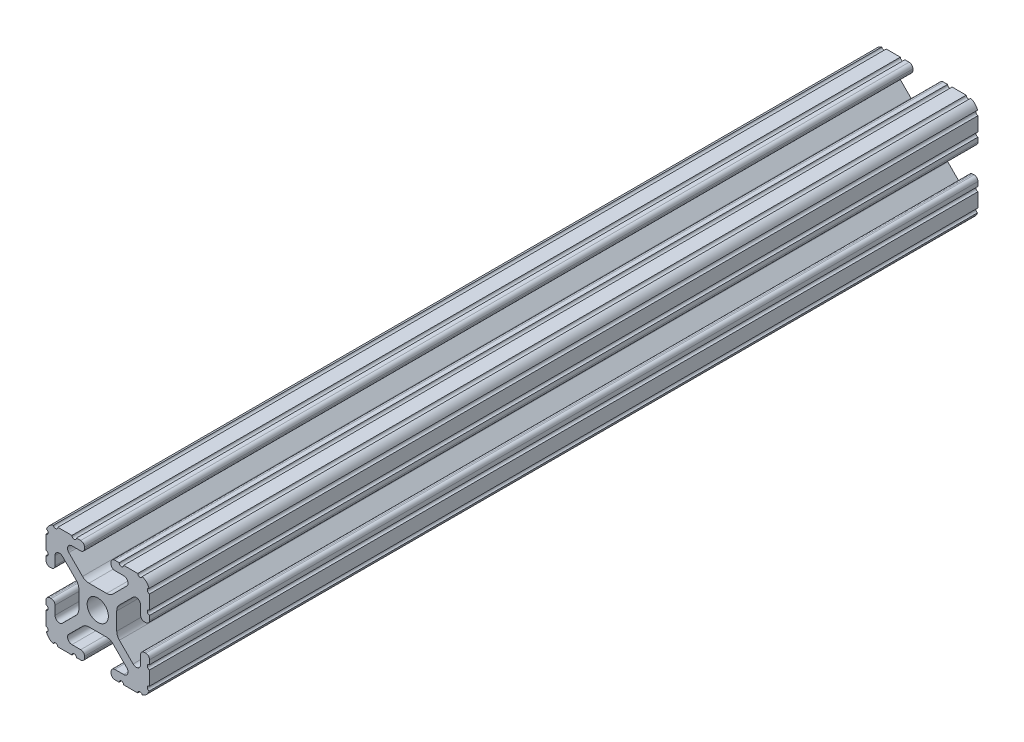
SolidWorks part; units mm, degrees
material "6061 Alloy"
ref_plane "Front Plane" through (0, 0, 0) normal (0, 0, 1) x (1, 0, 0)
ref_plane "Top Plane" through (0, 0, 0) normal (0, 1, 0) x (1, 0, 0)
ref_plane "Right Plane" through (0, 0, 0) normal (1, 0, 0) x (0, 0, -1)
sketch "Sketch2" plane through (0, 0, 0) normal (0, 0, 1) x (1, 0, 0)
  line L0 (0, 12.7) -> (0, -12.7) construction
  line L1 (-12.7, 0) -> (12.7, 0) construction
  line L2 (3.2512, -12.7) -> (12.7, -12.7)
  line L3 (12.7, -12.7) -> (12.7, -3.2512)
  line L4 (3.2512, -12.7) -> (3.2512, -10.4902)
  line L5 (3.2512, -10.4902) -> (8.9276, -10.4902)
  line L6 (8.9276, -10.4902) -> (3.0856, -4.6482)
  line L7 (0, 0) -> (12.7, -12.7) construction
  line L8 (12.7, -3.2512) -> (10.4902, -3.2512)
  line L9 (10.4902, -3.2512) -> (10.4902, -8.9276)
  line L10 (10.4902, -8.9276) -> (4.6482, -3.0856)
  circle A0 centre (0, 0) radius 2.6035
  arc A1 (6.3485, -10.4902) -> (7.1039, -8.6665) centre (6.3485, -9.4219) ccw construction
  point P8 (0, -4.6482)
  dimension "Center Hole Diameter" = 5.207
  dimension "Rail Height" = 25.4
  dimension "Rail Width" = 25.4
  dimension "T-Slot Width" = 6.5024
  dimension "Slot Inner Width" = 14.8336
  dimension "Thickness" = 2.2098
  dimension "Slot Depth" = 5.842
  dimension "D1" = 2.2098
sketch "Sketch3" plane through (0, 0, 0) normal (1, 0, 0) x (0, 0, -1)
  line L0 (-101.6, -12.7) -> (101.6, -12.7) construction
  line L1 (-76.2, 0) -> (76.2, 0) construction
  dimension "Length" = 203.2
  dimension "D1" = 25.4
sketch "Sketch4" plane through (0, 0, 0) normal (0, 0, 1) x (1, 0, 0)
  line L0 (4.1904, -12.7) -> (10.1173, -12.7)
  line L1 (3.2512, -12.7) -> (12.7, -12.7) construction
  line L2 (3.2512, -12.7) -> (3.2512, -10.4902) construction
  line L3 (3.2512, -10.4902) -> (8.9276, -10.4902) construction
  line L4 (3.2512, -11.4294) -> (3.2512, -11.7608)
  line L5 (4.1904, -10.4902) -> (6.3485, -10.4902)
  line L6 (0, -4.6482) -> (2.164, -4.6482)
  line L7 (8.9276, -10.4902) -> (3.0856, -4.6482) construction
  line L8 (3.7373, -5.2999) -> (7.1039, -8.6665)
  line L9 (12.7, -12.7) -> (12.7, -3.2512) construction
  line L10 (10.4902, -8.9276) -> (4.6482, -3.0856) construction
  line L11 (10.4902, -3.2512) -> (10.4902, -8.9276) construction
  line L12 (10.4902, -6.3485) -> (10.4902, -4.1904)
  line L13 (12.7, -3.2512) -> (10.4902, -3.2512) construction
  line L14 (11.4294, -3.2512) -> (11.7608, -3.2512)
  line L15 (12.7, -4.1904) -> (12.7, -10.1173)
  line L16 (8.6665, -7.1039) -> (5.2999, -3.7373)
  line L17 (4.6482, 0) -> (4.6482, -2.164)
  line L18 (-12.7, 0) -> (12.7, 0) construction
  line L19 (0, -4.6482) -> (0, -2.6035)
  line L20 (0, 12.7) -> (0, -12.7) construction
  line L21 (4.6482, 0) -> (2.6035, 0)
  arc A0 (3.2512, -11.7608) -> (4.1904, -12.7) centre (4.1904, -11.7608) ccw
  arc A2 (3.2512, -11.4294) -> (4.1904, -10.4902) centre (4.1904, -11.4294) cw
  arc A3 (6.3485, -10.4902) -> (7.1039, -8.6665) centre (6.3485, -9.4219) ccw
  arc A4 (2.164, -4.6482) -> (3.7373, -5.2999) centre (2.164, -6.8732) cw
  arc A5 (10.1173, -12.7) -> (12.7, -10.1173) centre (10.1173, -10.1173) ccw
  arc A6 (8.6665, -7.1039) -> (10.4902, -6.3485) centre (9.4219, -6.3485) ccw
  arc A7 (10.4902, -4.1904) -> (11.4294, -3.2512) centre (11.4294, -4.1904) cw
  arc A8 (11.7608, -3.2512) -> (12.7, -4.1904) centre (11.7608, -4.1904) cw
  arc A9 (5.2999, -3.7373) -> (4.6482, -2.164) centre (6.8732, -2.164) cw
  circle A10 centre (0, 0) radius 2.6035 construction
  arc A11 (0, -2.6035) -> (2.6035, 0) centre (0, 0) ccw
  dimension "D1" = 2.5827
  dimension "D2" = 2.225
  dimension "D3" = 0.9392
extrude "Boss-Extrude1" add sketch "Sketch4" along normal mid plane 203.2
sketch "Sketch5" plane through (0, 0, 0) normal (0, 0, 1) x (1, 0, 0)
  line L0 (3.2512, -12.7) -> (12.7, -12.7) construction
  line L1 (4.1904, -10.4902) -> (6.3485, -10.4902) construction
  line L3 (0, 0) -> (12.7, -12.7) construction
  line L4 (6.3485, -10.4902) -> (6.3485, -12.7) construction
  line L5 (8.9276, -10.4902) -> (3.0856, -4.6482) construction
  circle A0 centre (10.3562, -12.7) radius 0.5524
  circle A1 centre (5.796, -12.7) radius 0.5524
  circle A2 centre (12.7, -10.3562) radius 0.5524
  circle A3 centre (12.7, -5.796) radius 0.5524
  point P10 (5.2694, -10.4902)
  point P12 (9.4219, -6.3485)
  dimension "D1" = 1.1049
extrude "Cut-Extrude1" cut sketch "Sketch5" against normal through all both and the other way through all
mirror "Mirror1" about plane through (0, 0, 0) normal (1, 0, 0) of bodies 137 134
mirror "Mirror2" about plane through (0, 0, 0) normal (0, 1, 0) of bodies 135
equation "\"D1@Boss-Extrude1\"=\"Length@Sketch3\""
equation "\"D1@Sketch2\"=\"Thickness@Sketch2\""
equation "\"D2@Sketch4\"=\"Slot Inner Width@Sketch2\"*0.15"
equation "\"D1@Sketch4\"=\"D3@Sketch4\"*2.75"
equation "\"D3@Sketch4\"=\"Thickness@Sketch2\"*0.425"
equation "\"D1@Sketch5\"=\"Thickness@Sketch2\"*0.5"
